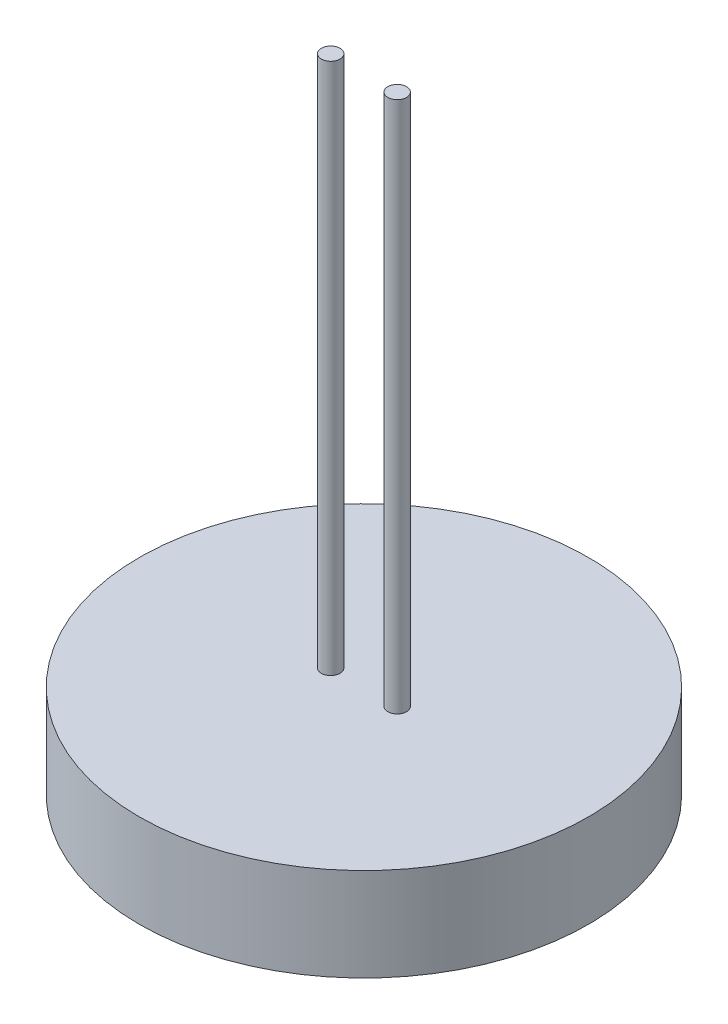
SolidWorks part; units mm, degrees
ref_plane "Front Plane" through (0, 0, 0) normal (0, 0, 1) x (1, 0, 0)
ref_plane "Top Plane" through (0, 0, 0) normal (0, 1, 0) x (1, 0, 0)
ref_plane "Right Plane" through (0, 0, 0) normal (1, 0, 0) x (0, 0, -1)
sketch "Sketch2" plane through (0, 0, 0) normal (0, 1, 0) x (1, 0, 0)
  circle A0 centre (0, 0) radius 16.891
  dimension "D1" = 33.782
extrude "Boss-Extrude1" add sketch "Sketch2" along normal blind 7
sketch "Sketch3" plane through (0, 7, 0) normal (0, 1, 0) x (1, 0, 0)
  line L0 (-2.5, 0) -> (0, 0) construction
  line L1 (2.5, 0) -> (0, 0) construction
  circle A0 centre (-2.5, 0) radius 0.7036
  circle A1 centre (2.5, 0) radius 0.7036
  dimension "D1" = 5
extrude "Boss-Extrude2" add sketch "Sketch3" along normal blind 40 and the other way blind 17
